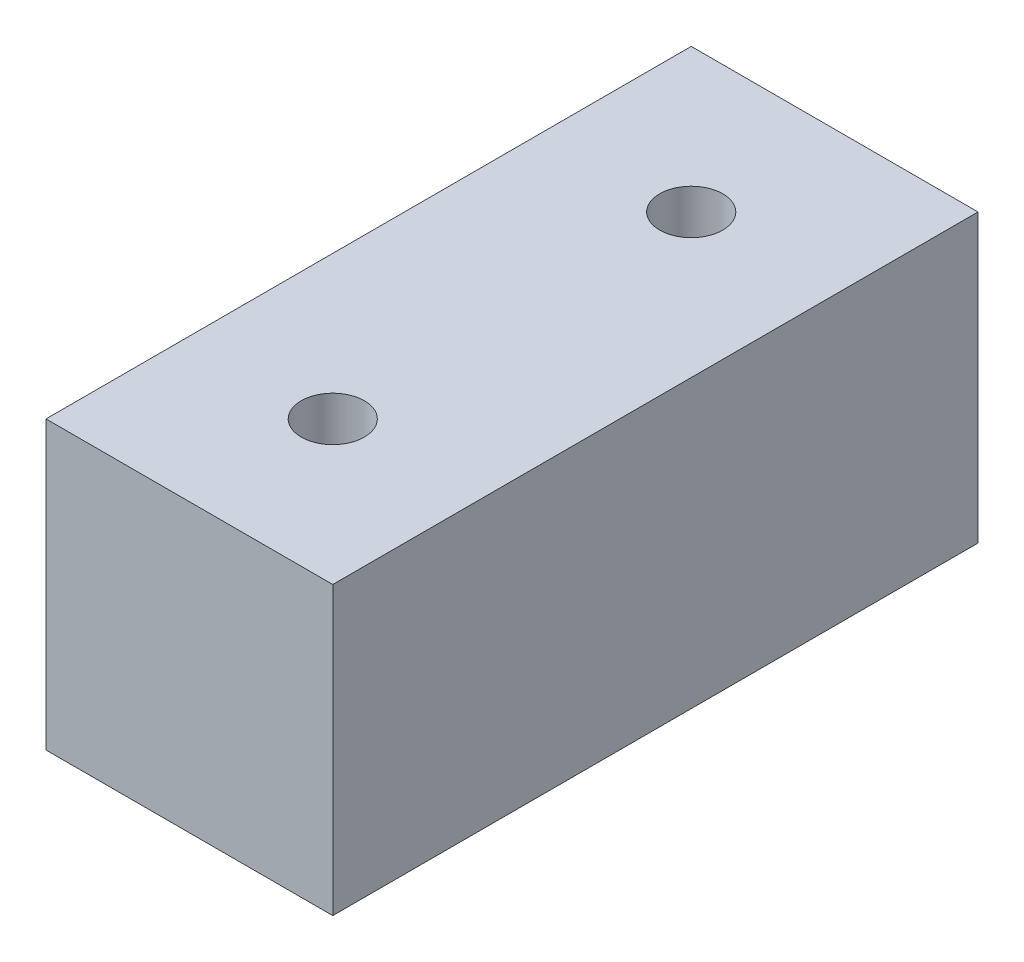
SolidWorks part; units mm, degrees
ref_plane "前视基准面" through (0, 0, 0) normal (0, 0, 1) x (1, 0, 0)
ref_plane "上视基准面" through (0, 0, 0) normal (0, 1, 0) x (1, 0, 0)
ref_plane "右视基准面" through (0, 0, 0) normal (1, 0, 0) x (0, 0, -1)
other "Configuration Table"
sketch "草图1" plane through (0, 0, 0) normal (0, 0, 1) x (1, 0, 0)
  line L1 (-10, 10) -> (10, 10)
  line L2 (-10, 10) -> (-10, -10)
  line L3 (-10, -10) -> (10, -10)
  line L4 (10, 10) -> (10, -10)
  line L5 (-10, 10) -> (10, -10) construction
  line L6 (-10, -10) -> (10, 10) construction
  point P0 (0, 0)
  dimension "D1" = 20
  dimension "D2" = 20
extrude "凸台-拉伸1" add sketch "草图1" along normal blind 45
sketch "草图2" plane through (0, 10, 0) normal (0, 1, 0) x (1, 0, 0)
  line L0 (0, 0) -> (0, -45) construction
  line L1 (10, -45) -> (-10, -45) construction
  circle A0 centre (0, -10) radius 2.2
  circle A1 centre (0, -35) radius 2.2
  point P9 (0, -14.4626)
  point P10 (0, -33.0685)
  point P13 (1.7574, -45)
  dimension "D1" = 4.4
  dimension "D2" = 25
  dimension "D3" = 10
extrude "切除-拉伸1" cut sketch "草图2" against normal blind 45
